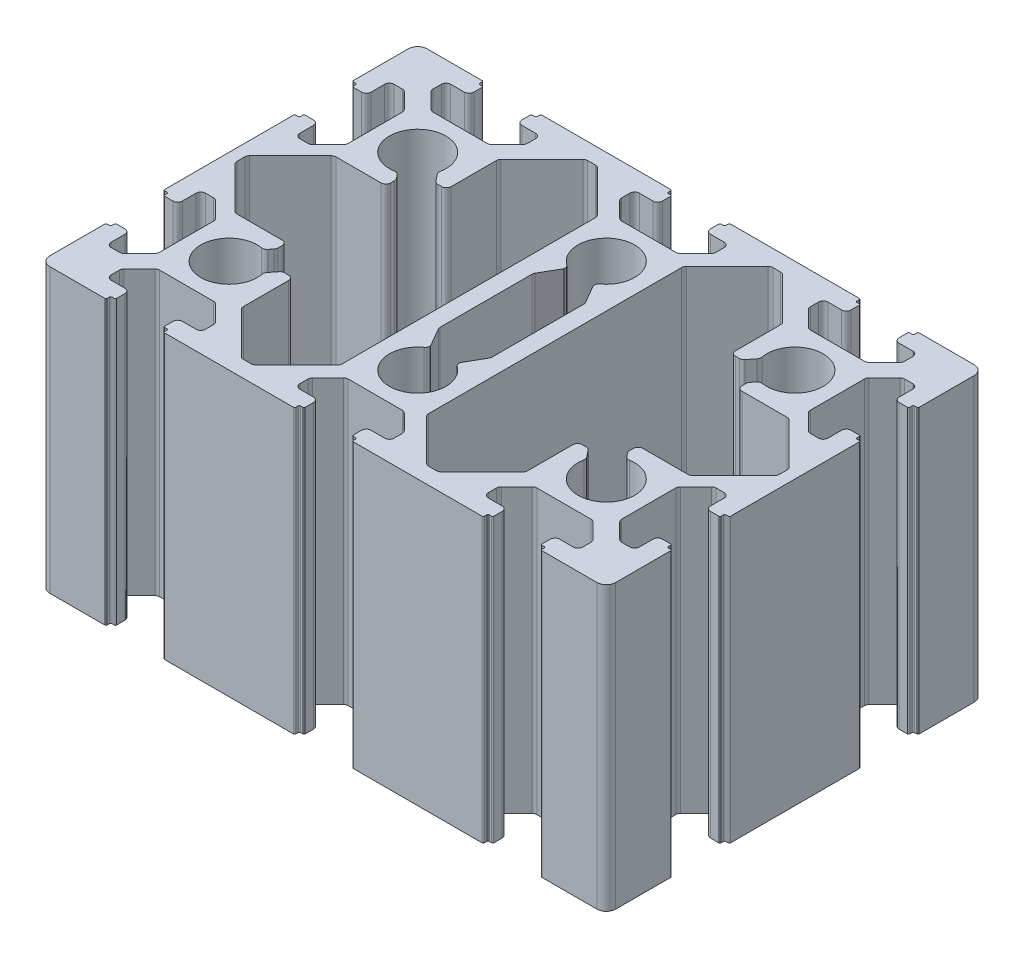
SolidWorks part; units mm, degrees
material "6061 Alloy"
ref_plane "Front Plane" through (0, 0, 0) normal (0, 0, 1) x (1, 0, 0)
ref_plane "Top Plane" through (0, 0, 0) normal (0, 1, 0) x (1, 0, 0)
ref_plane "Right Plane" through (0, 0, 0) normal (1, 0, 0) x (0, 0, -1)
sketch "Sketch2" plane through (0, 0, 0) normal (0, 1, 0) x (1, 0, 0)
  line L1 (60, -40) -> (-60, -40) construction
  line L2 (60, -40) -> (60, 40) construction
  line L3 (60, 40) -> (-60, 40) construction
  line L4 (-60, -40) -> (-60, 40) construction
  line L5 (60, -40) -> (-60, 40) construction
  line L6 (60, 40) -> (-60, -40) construction
  point P0 (0, 0)
  dimension "D1" = 120
  dimension "D2" = 80
sketch "Sketch5" plane through (0, 0, 0) normal (0, 1, 0) x (1, 0, 0)
  line L0 (0, 40) -> (0, -40) construction
  line L1 (60, 40) -> (-60, 40) construction
  line L2 (60, -40) -> (-60, -40) construction
  line L3 (-60, 0) -> (60, 0) construction
  line L4 (-60, -40) -> (-60, 40) construction
  line L5 (0, 40) -> (0, 29)
  line L6 (5.7358, 29) -> (-5.7358, 29)
  line L7 (-6.4429, 29.2929) -> (-9.7071, 32.5571)
  line L8 (-10, 33.2642) -> (-10, 35)
  line L9 (-9, 36) -> (-6.1, 36)
  line L10 (-5.1, 37) -> (-5.1, 38.75)
  line L11 (-5.35, 39) -> (-5.85, 39)
  line L12 (-6.1, 39.25) -> (-6.1, 39.75)
  line L13 (-6.35, 40) -> (-33.65, 40)
  line L14 (-33.9, 39.75) -> (-33.9, 39.25)
  line L15 (-34.15, 39) -> (-34.65, 39)
  line L16 (-34.9, 38.75) -> (-34.9, 37)
  line L17 (-33.9, 36) -> (-31, 36)
  line L18 (-30, 35) -> (-30, 33.2642)
  line L19 (-30.2929, 32.5571) -> (-33.5571, 29.2929)
  line L20 (-34.2642, 29) -> (-45.7358, 29)
  line L21 (-46.4429, 29.2929) -> (-49.7071, 32.5571)
  line L22 (-50, 33.2642) -> (-50, 35)
  line L23 (-49, 36) -> (-46.1, 36)
  line L24 (-45.1, 37) -> (-45.1, 38.75)
  line L25 (-45.35, 39) -> (-45.85, 39)
  line L26 (-46.1, 39.25) -> (-46.1, 39.75)
  line L27 (-46.35, 40) -> (-58, 40)
  line L28 (-60, 38) -> (-60, 26.35)
  line L29 (-59.75, 26.1) -> (-59.25, 26.1)
  line L30 (-59, 25.85) -> (-59, 25.35)
  line L31 (-58.75, 25.1) -> (-57, 25.1)
  line L32 (-56, 26.1) -> (-56, 29)
  line L33 (-55, 30) -> (-53.2642, 30)
  line L34 (-52.5571, 29.7071) -> (-49.2929, 26.4429)
  line L35 (-49, 25.7358) -> (-49, 14.2642)
  line L36 (-49.2929, 13.5571) -> (-52.5571, 10.2929)
  line L37 (-53.2642, 10) -> (-55, 10)
  line L38 (-56, 11) -> (-56, 13.9)
  line L39 (-57, 14.9) -> (-58.75, 14.9)
  line L40 (-59, 14.65) -> (-59, 14.15)
  line L41 (-59.25, 13.9) -> (-59.75, 13.9)
  line L42 (-60, 13.65) -> (-60, -13.65)
  line L43 (-40, 29) -> (-40, 40) construction
  line L44 (-49, 20) -> (-60, 20) construction
  line L45 (-60, 0) -> (-57.5, 0)
  line L46 (-57.5, -0.8358) -> (-57.5, 0.8358)
  line L47 (-57.2071, 1.5429) -> (-48.5429, 10.2071)
  line L48 (-47.8358, 10.5) -> (-38.25, 10.5)
  line L49 (-37.25, 11.5) -> (-37.25, 12.3383)
  line L50 (-40, 20) -> (-20, 0) construction
  line L51 (-34.2044, 18.4471) -> (-40, 20) construction
  line L52 (-30.15, 17.25) -> (-30.15, 26.8358)
  line L53 (-29.8571, 27.5429) -> (-21.1929, 36.2071)
  line L54 (-20.4858, 36.5) -> (-18.8142, 36.5)
  line L55 (-18.1071, 36.2071) -> (-9.4429, 27.5429)
  line L56 (-9.15, 26.8358) -> (-9.15, -26.8358)
  line L57 (-40, 20) -> (-38.4471, 14.2044) construction
  line L58 (-40, 20) -> (-44.2426, 24.2426) construction
  line L59 (-38.0611, 13.7145) -> (-37.4645, 12.9572)
  line L60 (-33.909, 18.0721) -> (-32.7739, 16.6312)
  line L61 (-31.9883, 16.25) -> (-31.15, 16.25)
  line L62 (-9.15, 0) -> (-5.5, 0) construction
  line L63 (-5.5, -9.7321) -> (-5.5, 9.7321)
  line L64 (-5.366, 10.2321) -> (-3.1188, 14.1243)
  line L65 (-3.1188, 14.1243) -> (-3.1188, 14.34)
  line L66 (0, 29) -> (0, 26) construction
  line L67 (-40, -20) -> (-44.2426, -24.2426) construction
  line L68 (-40, -20) -> (-38.4471, -14.2044) construction
  line L69 (-34.2044, -18.4471) -> (-40, -20) construction
  line L70 (-40, -20) -> (-20, 0) construction
  line L71 (-49, -20) -> (-60, -20) construction
  line L72 (-40, -29) -> (-40, -40) construction
  line L73 (0, -29) -> (0, -26) construction
  line L74 (-3.1188, -14.1243) -> (-3.1188, -14.34)
  line L75 (-5.366, -10.2321) -> (-3.1188, -14.1243)
  line L76 (-31.9883, -16.25) -> (-31.15, -16.25)
  line L77 (-33.909, -18.0721) -> (-32.7739, -16.6312)
  line L78 (-38.0611, -13.7145) -> (-37.4645, -12.9572)
  line L79 (-18.1071, -36.2071) -> (-9.4429, -27.5429)
  line L80 (-20.4858, -36.5) -> (-18.8142, -36.5)
  line L81 (-29.8571, -27.5429) -> (-21.1929, -36.2071)
  line L82 (-30.15, -17.25) -> (-30.15, -26.8358)
  line L83 (-37.25, -11.5) -> (-37.25, -12.3383)
  line L84 (-47.8358, -10.5) -> (-38.25, -10.5)
  line L85 (-57.2071, -1.5429) -> (-48.5429, -10.2071)
  line L86 (-59.25, -13.9) -> (-59.75, -13.9)
  line L87 (-59, -14.65) -> (-59, -14.15)
  line L88 (-57, -14.9) -> (-58.75, -14.9)
  line L89 (-56, -11) -> (-56, -13.9)
  line L90 (-53.2642, -10) -> (-55, -10)
  line L91 (-49.2929, -13.5571) -> (-52.5571, -10.2929)
  line L92 (-49, -25.7358) -> (-49, -14.2642)
  line L93 (-52.5571, -29.7071) -> (-49.2929, -26.4429)
  line L94 (-55, -30) -> (-53.2642, -30)
  line L95 (-56, -26.1) -> (-56, -29)
  line L96 (-58.75, -25.1) -> (-57, -25.1)
  line L97 (-59, -25.85) -> (-59, -25.35)
  line L98 (-59.75, -26.1) -> (-59.25, -26.1)
  line L99 (-60, -38) -> (-60, -26.35)
  line L100 (-46.35, -40) -> (-58, -40)
  line L101 (-46.1, -39.25) -> (-46.1, -39.75)
  line L102 (-45.35, -39) -> (-45.85, -39)
  line L103 (-45.1, -37) -> (-45.1, -38.75)
  line L104 (-49, -36) -> (-46.1, -36)
  line L105 (-50, -33.2642) -> (-50, -35)
  line L106 (-46.4429, -29.2929) -> (-49.7071, -32.5571)
  line L107 (-34.2642, -29) -> (-45.7358, -29)
  line L108 (-30.2929, -32.5571) -> (-33.5571, -29.2929)
  line L109 (-30, -35) -> (-30, -33.2642)
  line L110 (-33.9, -36) -> (-31, -36)
  line L111 (-34.9, -38.75) -> (-34.9, -37)
  line L112 (-34.15, -39) -> (-34.65, -39)
  line L113 (-33.9, -39.75) -> (-33.9, -39.25)
  line L114 (-6.35, -40) -> (-33.65, -40)
  line L115 (-6.1, -39.25) -> (-6.1, -39.75)
  line L116 (-5.35, -39) -> (-5.85, -39)
  line L117 (-5.1, -37) -> (-5.1, -38.75)
  line L118 (-9, -36) -> (-6.1, -36)
  line L119 (-10, -33.2642) -> (-10, -35)
  line L120 (-6.4429, -29.2929) -> (-9.7071, -32.5571)
  line L121 (5.7358, -29) -> (-5.7358, -29)
  line L122 (0, -40) -> (0, -29)
  line L123 (40, -29) -> (40, -40) construction
  line L124 (49, -20) -> (60, -20) construction
  line L125 (40, -20) -> (20, 0) construction
  line L126 (34.2044, -18.4471) -> (40, -20) construction
  line L127 (40, -20) -> (38.4471, -14.2044) construction
  line L128 (40, -20) -> (44.2426, -24.2426) construction
  line L129 (40, 20) -> (44.2426, 24.2426) construction
  line L130 (40, 20) -> (38.4471, 14.2044) construction
  line L131 (34.2044, 18.4471) -> (40, 20) construction
  line L132 (40, 20) -> (20, 0) construction
  line L133 (49, 20) -> (60, 20) construction
  line L134 (40, 29) -> (40, 40) construction
  line L135 (6.4429, -29.2929) -> (9.7071, -32.5571)
  line L136 (10, -33.2642) -> (10, -35)
  line L137 (9, -36) -> (6.1, -36)
  line L138 (5.1, -37) -> (5.1, -38.75)
  line L139 (5.35, -39) -> (5.85, -39)
  line L140 (6.1, -39.25) -> (6.1, -39.75)
  line L141 (6.35, -40) -> (33.65, -40)
  line L142 (33.9, -39.75) -> (33.9, -39.25)
  line L143 (34.15, -39) -> (34.65, -39)
  line L144 (34.9, -38.75) -> (34.9, -37)
  line L145 (33.9, -36) -> (31, -36)
  line L146 (30, -35) -> (30, -33.2642)
  line L147 (30.2929, -32.5571) -> (33.5571, -29.2929)
  line L148 (34.2642, -29) -> (45.7358, -29)
  line L149 (46.4429, -29.2929) -> (49.7071, -32.5571)
  line L150 (50, -33.2642) -> (50, -35)
  line L151 (49, -36) -> (46.1, -36)
  line L152 (45.1, -37) -> (45.1, -38.75)
  line L153 (45.35, -39) -> (45.85, -39)
  line L154 (46.1, -39.25) -> (46.1, -39.75)
  line L155 (46.35, -40) -> (58, -40)
  line L156 (60, -38) -> (60, -26.35)
  line L157 (59.75, -26.1) -> (59.25, -26.1)
  line L158 (59, -25.85) -> (59, -25.35)
  line L159 (58.75, -25.1) -> (57, -25.1)
  line L160 (56, -26.1) -> (56, -29)
  line L161 (55, -30) -> (53.2642, -30)
  line L162 (52.5571, -29.7071) -> (49.2929, -26.4429)
  line L163 (49, -25.7358) -> (49, -14.2642)
  line L164 (49.2929, -13.5571) -> (52.5571, -10.2929)
  line L165 (53.2642, -10) -> (55, -10)
  line L166 (56, -11) -> (56, -13.9)
  line L167 (57, -14.9) -> (58.75, -14.9)
  line L168 (59, -14.65) -> (59, -14.15)
  line L169 (59.25, -13.9) -> (59.75, -13.9)
  line L170 (57.2071, -1.5429) -> (48.5429, -10.2071)
  line L171 (47.8358, -10.5) -> (38.25, -10.5)
  line L172 (37.25, -11.5) -> (37.25, -12.3383)
  line L173 (30.15, -17.25) -> (30.15, -26.8358)
  line L174 (29.8571, -27.5429) -> (21.1929, -36.2071)
  line L175 (20.4858, -36.5) -> (18.8142, -36.5)
  line L176 (18.1071, -36.2071) -> (9.4429, -27.5429)
  line L177 (38.0611, -13.7145) -> (37.4645, -12.9572)
  line L178 (33.909, -18.0721) -> (32.7739, -16.6312)
  line L179 (31.9883, -16.25) -> (31.15, -16.25)
  line L180 (5.366, -10.2321) -> (3.1188, -14.1243)
  line L181 (3.1188, -14.1243) -> (3.1188, -14.34)
  line L182 (3.1188, 14.1243) -> (3.1188, 14.34)
  line L183 (5.366, 10.2321) -> (3.1188, 14.1243)
  line L184 (5.5, -9.7321) -> (5.5, 9.7321)
  line L185 (9.15, 0) -> (5.5, 0) construction
  line L186 (31.9883, 16.25) -> (31.15, 16.25)
  line L187 (33.909, 18.0721) -> (32.7739, 16.6312)
  line L188 (38.0611, 13.7145) -> (37.4645, 12.9572)
  line L189 (9.15, 26.8358) -> (9.15, -26.8358)
  line L190 (18.1071, 36.2071) -> (9.4429, 27.5429)
  line L191 (20.4858, 36.5) -> (18.8142, 36.5)
  line L192 (29.8571, 27.5429) -> (21.1929, 36.2071)
  line L193 (30.15, 17.25) -> (30.15, 26.8358)
  line L194 (37.25, 11.5) -> (37.25, 12.3383)
  line L195 (47.8358, 10.5) -> (38.25, 10.5)
  line L196 (57.2071, 1.5429) -> (48.5429, 10.2071)
  line L197 (57.5, -0.8358) -> (57.5, 0.8358)
  line L198 (60, 0) -> (57.5, 0)
  line L199 (60, 13.65) -> (60, -13.65)
  line L200 (59.25, 13.9) -> (59.75, 13.9)
  line L201 (59, 14.65) -> (59, 14.15)
  line L202 (57, 14.9) -> (58.75, 14.9)
  line L203 (56, 11) -> (56, 13.9)
  line L204 (53.2642, 10) -> (55, 10)
  line L205 (49.2929, 13.5571) -> (52.5571, 10.2929)
  line L206 (49, 25.7358) -> (49, 14.2642)
  line L207 (52.5571, 29.7071) -> (49.2929, 26.4429)
  line L208 (55, 30) -> (53.2642, 30)
  line L209 (56, 26.1) -> (56, 29)
  line L210 (58.75, 25.1) -> (57, 25.1)
  line L211 (59, 25.85) -> (59, 25.35)
  line L212 (59.75, 26.1) -> (59.25, 26.1)
  line L213 (60, 38) -> (60, 26.35)
  line L214 (46.35, 40) -> (58, 40)
  line L215 (46.1, 39.25) -> (46.1, 39.75)
  line L216 (45.35, 39) -> (45.85, 39)
  line L217 (45.1, 37) -> (45.1, 38.75)
  line L218 (49, 36) -> (46.1, 36)
  line L219 (50, 33.2642) -> (50, 35)
  line L220 (46.4429, 29.2929) -> (49.7071, 32.5571)
  line L221 (34.2642, 29) -> (45.7358, 29)
  line L222 (30.2929, 32.5571) -> (33.5571, 29.2929)
  line L223 (30, 35) -> (30, 33.2642)
  line L224 (33.9, 36) -> (31, 36)
  line L225 (34.9, 38.75) -> (34.9, 37)
  line L226 (34.15, 39) -> (34.65, 39)
  line L227 (33.9, 39.75) -> (33.9, 39.25)
  line L228 (6.35, 40) -> (33.65, 40)
  line L229 (6.1, 39.25) -> (6.1, 39.75)
  line L230 (5.35, 39) -> (5.85, 39)
  line L231 (5.1, 37) -> (5.1, 38.75)
  line L232 (9, 36) -> (6.1, 36)
  line L233 (10, 33.2642) -> (10, 35)
  line L234 (6.4429, 29.2929) -> (9.7071, 32.5571)
  arc A0 (-34.1059, 18.8779) -> (-39.0114, 14.082) centre (-40, 20) ccw
  arc A1 (3.5304, 15.1486) -> (-3.5304, 15.1486) centre (0, 20) ccw
  arc A2 (-56, 13.9) -> (-57, 14.9) centre (-57, 13.9) ccw
  arc A3 (-6.1, 36) -> (-5.1, 37) centre (-6.1, 37) ccw
  arc A4 (-5.7358, 29) -> (-6.4429, 29.2929) centre (-5.7358, 30) cw
  arc A5 (-9.7071, 32.5571) -> (-10, 33.2642) centre (-9, 33.2642) cw
  arc A6 (-10, 35) -> (-9, 36) centre (-9, 35) cw
  arc A7 (-5.5, 9.7321) -> (-5.366, 10.2321) centre (-4.5, 9.7321) cw
  arc A8 (-3.1188, 14.34) -> (-3.5304, 15.1486) centre (-4.1188, 14.34) ccw
  arc A9 (-39.0114, 14.082) -> (-38.0611, 13.7145) centre (-38.8466, 13.0957) cw
  arc A10 (-37.25, 12.3383) -> (-37.4645, 12.9572) centre (-38.25, 12.3383) ccw
  arc A11 (-38.25, 10.5) -> (-37.25, 11.5) centre (-38.25, 11.5) ccw
  arc A12 (-34.1059, 18.8779) -> (-33.909, 18.0721) centre (-33.1235, 18.6909) ccw
  arc A13 (-32.7739, 16.6312) -> (-31.9883, 16.25) centre (-31.9883, 17.25) ccw
  arc A14 (-31.15, 16.25) -> (-30.15, 17.25) centre (-31.15, 17.25) ccw
  arc A15 (-48.5429, 10.2071) -> (-47.8358, 10.5) centre (-47.8358, 9.5) cw
  arc A16 (-18.8142, 36.5) -> (-18.1071, 36.2071) centre (-18.8142, 35.5) cw
  arc A17 (-21.1929, 36.2071) -> (-20.4858, 36.5) centre (-20.4858, 35.5) cw
  arc A18 (-30.15, 26.8358) -> (-29.8571, 27.5429) centre (-29.15, 26.8358) cw
  arc A19 (-9.4429, 27.5429) -> (-9.15, 26.8358) centre (-10.15, 26.8358) cw
  arc A20 (-34.9, 37) -> (-33.9, 36) centre (-33.9, 37) ccw
  arc A21 (-46.1, 36) -> (-45.1, 37) centre (-46.1, 37) ccw
  arc A22 (-30, 33.2642) -> (-30.2929, 32.5571) centre (-31, 33.2642) cw
  arc A23 (-31, 36) -> (-30, 35) centre (-31, 35) cw
  arc A24 (-50, 35) -> (-49, 36) centre (-49, 35) cw
  arc A25 (-49.7071, 32.5571) -> (-50, 33.2642) centre (-49, 33.2642) cw
  arc A26 (-45.7358, 29) -> (-46.4429, 29.2929) centre (-45.7358, 30) cw
  arc A27 (-33.5571, 29.2929) -> (-34.2642, 29) centre (-34.2642, 30) cw
  arc A28 (-57, 25.1) -> (-56, 26.1) centre (-57, 26.1) ccw
  arc A29 (-56, 29) -> (-55, 30) centre (-55, 29) cw
  arc A30 (-53.2642, 30) -> (-52.5571, 29.7071) centre (-53.2642, 29) cw
  arc A31 (-49.2929, 26.4429) -> (-49, 25.7358) centre (-50, 25.7358) cw
  arc A32 (-49, 14.2642) -> (-49.2929, 13.5571) centre (-50, 14.2642) cw
  arc A33 (-52.5571, 10.2929) -> (-53.2642, 10) centre (-53.2642, 11) cw
  arc A34 (-55, 10) -> (-56, 11) centre (-55, 11) cw
  arc A35 (-6.1, 39.75) -> (-6.35, 40) centre (-6.35, 39.75) ccw
  arc A36 (-5.85, 39) -> (-6.1, 39.25) centre (-5.85, 39.25) cw
  arc A37 (-5.1, 38.75) -> (-5.35, 39) centre (-5.35, 38.75) ccw
  arc A38 (-33.65, 40) -> (-33.9, 39.75) centre (-33.65, 39.75) ccw
  arc A39 (-34.65, 39) -> (-34.9, 38.75) centre (-34.65, 38.75) ccw
  arc A40 (-33.9, 39.25) -> (-34.15, 39) centre (-34.15, 39.25) cw
  arc A41 (-46.1, 39.75) -> (-46.35, 40) centre (-46.35, 39.75) ccw
  arc A42 (-45.85, 39) -> (-46.1, 39.25) centre (-45.85, 39.25) cw
  arc A43 (-45.1, 38.75) -> (-45.35, 39) centre (-45.35, 38.75) ccw
  arc A44 (-60, 26.35) -> (-59.75, 26.1) centre (-59.75, 26.35) ccw
  arc A45 (-59.25, 26.1) -> (-59, 25.85) centre (-59.25, 25.85) cw
  arc A46 (-59, 25.35) -> (-58.75, 25.1) centre (-58.75, 25.35) ccw
  arc A47 (-58.75, 14.9) -> (-59, 14.65) centre (-58.75, 14.65) ccw
  arc A48 (-59, 14.15) -> (-59.25, 13.9) centre (-59.25, 14.15) cw
  arc A49 (-59.75, 13.9) -> (-60, 13.65) centre (-59.75, 13.65) ccw
  arc A50 (-57.5, 0.8358) -> (-57.2071, 1.5429) centre (-56.5, 0.8358) cw
  arc A51 (-58, 40) -> (-60, 38) centre (-58, 38) ccw
  arc A52 (-58, -40) -> (-60, -38) centre (-58, -38) cw
  arc A53 (-57.5, -0.8358) -> (-57.2071, -1.5429) centre (-56.5, -0.8358) ccw
  arc A54 (-59.75, -13.9) -> (-60, -13.65) centre (-59.75, -13.65) cw
  arc A55 (-59, -14.15) -> (-59.25, -13.9) centre (-59.25, -14.15) ccw
  arc A56 (-58.75, -14.9) -> (-59, -14.65) centre (-58.75, -14.65) cw
  arc A57 (-59, -25.35) -> (-58.75, -25.1) centre (-58.75, -25.35) cw
  arc A58 (-59.25, -26.1) -> (-59, -25.85) centre (-59.25, -25.85) ccw
  arc A59 (-60, -26.35) -> (-59.75, -26.1) centre (-59.75, -26.35) cw
  arc A60 (-45.1, -38.75) -> (-45.35, -39) centre (-45.35, -38.75) cw
  arc A61 (-45.85, -39) -> (-46.1, -39.25) centre (-45.85, -39.25) ccw
  arc A62 (-46.1, -39.75) -> (-46.35, -40) centre (-46.35, -39.75) cw
  arc A63 (-33.9, -39.25) -> (-34.15, -39) centre (-34.15, -39.25) ccw
  arc A64 (-34.65, -39) -> (-34.9, -38.75) centre (-34.65, -38.75) cw
  arc A65 (-33.65, -40) -> (-33.9, -39.75) centre (-33.65, -39.75) cw
  arc A66 (-5.1, -38.75) -> (-5.35, -39) centre (-5.35, -38.75) cw
  arc A67 (-5.85, -39) -> (-6.1, -39.25) centre (-5.85, -39.25) ccw
  arc A68 (-6.1, -39.75) -> (-6.35, -40) centre (-6.35, -39.75) cw
  arc A69 (-55, -10) -> (-56, -11) centre (-55, -11) ccw
  arc A70 (-52.5571, -10.2929) -> (-53.2642, -10) centre (-53.2642, -11) ccw
  arc A71 (-49, -14.2642) -> (-49.2929, -13.5571) centre (-50, -14.2642) ccw
  arc A72 (-49.2929, -26.4429) -> (-49, -25.7358) centre (-50, -25.7358) ccw
  arc A73 (-53.2642, -30) -> (-52.5571, -29.7071) centre (-53.2642, -29) ccw
  arc A74 (-56, -29) -> (-55, -30) centre (-55, -29) ccw
  arc A75 (-57, -25.1) -> (-56, -26.1) centre (-57, -26.1) cw
  arc A76 (-33.5571, -29.2929) -> (-34.2642, -29) centre (-34.2642, -30) ccw
  arc A77 (-45.7358, -29) -> (-46.4429, -29.2929) centre (-45.7358, -30) ccw
  arc A78 (-49.7071, -32.5571) -> (-50, -33.2642) centre (-49, -33.2642) ccw
  arc A79 (-50, -35) -> (-49, -36) centre (-49, -35) ccw
  arc A80 (-31, -36) -> (-30, -35) centre (-31, -35) ccw
  arc A81 (-30, -33.2642) -> (-30.2929, -32.5571) centre (-31, -33.2642) ccw
  arc A82 (-46.1, -36) -> (-45.1, -37) centre (-46.1, -37) cw
  arc A83 (-34.9, -37) -> (-33.9, -36) centre (-33.9, -37) cw
  arc A84 (-9.4429, -27.5429) -> (-9.15, -26.8358) centre (-10.15, -26.8358) ccw
  arc A85 (-30.15, -26.8358) -> (-29.8571, -27.5429) centre (-29.15, -26.8358) ccw
  arc A86 (-21.1929, -36.2071) -> (-20.4858, -36.5) centre (-20.4858, -35.5) ccw
  arc A87 (-18.8142, -36.5) -> (-18.1071, -36.2071) centre (-18.8142, -35.5) ccw
  arc A88 (-48.5429, -10.2071) -> (-47.8358, -10.5) centre (-47.8358, -9.5) ccw
  arc A89 (-31.15, -16.25) -> (-30.15, -17.25) centre (-31.15, -17.25) cw
  arc A90 (-32.7739, -16.6312) -> (-31.9883, -16.25) centre (-31.9883, -17.25) cw
  arc A91 (-34.1059, -18.8779) -> (-33.909, -18.0721) centre (-33.1235, -18.6909) cw
  arc A92 (-38.25, -10.5) -> (-37.25, -11.5) centre (-38.25, -11.5) cw
  arc A93 (-37.25, -12.3383) -> (-37.4645, -12.9572) centre (-38.25, -12.3383) cw
  arc A94 (-39.0114, -14.082) -> (-38.0611, -13.7145) centre (-38.8466, -13.0957) ccw
  arc A95 (-3.1188, -14.34) -> (-3.5304, -15.1486) centre (-4.1188, -14.34) cw
  arc A96 (-5.5, -9.7321) -> (-5.366, -10.2321) centre (-4.5, -9.7321) ccw
  arc A97 (-10, -35) -> (-9, -36) centre (-9, -35) ccw
  arc A98 (-9.7071, -32.5571) -> (-10, -33.2642) centre (-9, -33.2642) ccw
  arc A99 (-5.7358, -29) -> (-6.4429, -29.2929) centre (-5.7358, -30) ccw
  arc A100 (-6.1, -36) -> (-5.1, -37) centre (-6.1, -37) cw
  arc A101 (-56, -13.9) -> (-57, -14.9) centre (-57, -13.9) cw
  arc A102 (3.5304, -15.1486) -> (-3.5304, -15.1486) centre (0, -20) cw
  arc A103 (-34.1059, -18.8779) -> (-39.0114, -14.082) centre (-40, -20) cw
  arc A104 (34.1059, -18.8779) -> (39.0114, -14.082) centre (40, -20) ccw
  arc A105 (56, -13.9) -> (57, -14.9) centre (57, -13.9) ccw
  arc A106 (6.1, -36) -> (5.1, -37) centre (6.1, -37) ccw
  arc A107 (5.7358, -29) -> (6.4429, -29.2929) centre (5.7358, -30) cw
  arc A108 (9.7071, -32.5571) -> (10, -33.2642) centre (9, -33.2642) cw
  arc A109 (10, -35) -> (9, -36) centre (9, -35) cw
  arc A110 (5.5, -9.7321) -> (5.366, -10.2321) centre (4.5, -9.7321) cw
  arc A111 (3.1188, -14.34) -> (3.5304, -15.1486) centre (4.1188, -14.34) ccw
  arc A112 (39.0114, -14.082) -> (38.0611, -13.7145) centre (38.8466, -13.0957) cw
  arc A113 (37.25, -12.3383) -> (37.4645, -12.9572) centre (38.25, -12.3383) ccw
  arc A114 (38.25, -10.5) -> (37.25, -11.5) centre (38.25, -11.5) ccw
  arc A115 (34.1059, -18.8779) -> (33.909, -18.0721) centre (33.1235, -18.6909) ccw
  arc A116 (32.7739, -16.6312) -> (31.9883, -16.25) centre (31.9883, -17.25) ccw
  arc A117 (31.15, -16.25) -> (30.15, -17.25) centre (31.15, -17.25) ccw
  arc A118 (48.5429, -10.2071) -> (47.8358, -10.5) centre (47.8358, -9.5) cw
  arc A119 (18.8142, -36.5) -> (18.1071, -36.2071) centre (18.8142, -35.5) cw
  arc A120 (21.1929, -36.2071) -> (20.4858, -36.5) centre (20.4858, -35.5) cw
  arc A121 (30.15, -26.8358) -> (29.8571, -27.5429) centre (29.15, -26.8358) cw
  arc A122 (9.4429, -27.5429) -> (9.15, -26.8358) centre (10.15, -26.8358) cw
  arc A123 (34.9, -37) -> (33.9, -36) centre (33.9, -37) ccw
  arc A124 (46.1, -36) -> (45.1, -37) centre (46.1, -37) ccw
  arc A125 (30, -33.2642) -> (30.2929, -32.5571) centre (31, -33.2642) cw
  arc A126 (31, -36) -> (30, -35) centre (31, -35) cw
  arc A127 (50, -35) -> (49, -36) centre (49, -35) cw
  arc A128 (49.7071, -32.5571) -> (50, -33.2642) centre (49, -33.2642) cw
  arc A129 (45.7358, -29) -> (46.4429, -29.2929) centre (45.7358, -30) cw
  arc A130 (33.5571, -29.2929) -> (34.2642, -29) centre (34.2642, -30) cw
  arc A131 (57, -25.1) -> (56, -26.1) centre (57, -26.1) ccw
  arc A132 (56, -29) -> (55, -30) centre (55, -29) cw
  arc A133 (53.2642, -30) -> (52.5571, -29.7071) centre (53.2642, -29) cw
  arc A134 (49.2929, -26.4429) -> (49, -25.7358) centre (50, -25.7358) cw
  arc A135 (49, -14.2642) -> (49.2929, -13.5571) centre (50, -14.2642) cw
  arc A136 (52.5571, -10.2929) -> (53.2642, -10) centre (53.2642, -11) cw
  arc A137 (55, -10) -> (56, -11) centre (55, -11) cw
  arc A138 (6.1, -39.75) -> (6.35, -40) centre (6.35, -39.75) ccw
  arc A139 (5.85, -39) -> (6.1, -39.25) centre (5.85, -39.25) cw
  arc A140 (5.1, -38.75) -> (5.35, -39) centre (5.35, -38.75) ccw
  arc A141 (33.65, -40) -> (33.9, -39.75) centre (33.65, -39.75) ccw
  arc A142 (34.65, -39) -> (34.9, -38.75) centre (34.65, -38.75) ccw
  arc A143 (33.9, -39.25) -> (34.15, -39) centre (34.15, -39.25) cw
  arc A144 (46.1, -39.75) -> (46.35, -40) centre (46.35, -39.75) ccw
  arc A145 (45.85, -39) -> (46.1, -39.25) centre (45.85, -39.25) cw
  arc A146 (45.1, -38.75) -> (45.35, -39) centre (45.35, -38.75) ccw
  arc A147 (60, -26.35) -> (59.75, -26.1) centre (59.75, -26.35) ccw
  arc A148 (59.25, -26.1) -> (59, -25.85) centre (59.25, -25.85) cw
  arc A149 (59, -25.35) -> (58.75, -25.1) centre (58.75, -25.35) ccw
  arc A150 (58.75, -14.9) -> (59, -14.65) centre (58.75, -14.65) ccw
  arc A151 (59, -14.15) -> (59.25, -13.9) centre (59.25, -14.15) cw
  arc A152 (59.75, -13.9) -> (60, -13.65) centre (59.75, -13.65) ccw
  arc A153 (57.5, -0.8358) -> (57.2071, -1.5429) centre (56.5, -0.8358) cw
  arc A154 (58, -40) -> (60, -38) centre (58, -38) ccw
  arc A155 (58, 40) -> (60, 38) centre (58, 38) cw
  arc A156 (57.5, 0.8358) -> (57.2071, 1.5429) centre (56.5, 0.8358) ccw
  arc A157 (59.75, 13.9) -> (60, 13.65) centre (59.75, 13.65) cw
  arc A158 (59, 14.15) -> (59.25, 13.9) centre (59.25, 14.15) ccw
  arc A159 (58.75, 14.9) -> (59, 14.65) centre (58.75, 14.65) cw
  arc A160 (59, 25.35) -> (58.75, 25.1) centre (58.75, 25.35) cw
  arc A161 (59.25, 26.1) -> (59, 25.85) centre (59.25, 25.85) ccw
  arc A162 (60, 26.35) -> (59.75, 26.1) centre (59.75, 26.35) cw
  arc A163 (45.1, 38.75) -> (45.35, 39) centre (45.35, 38.75) cw
  arc A164 (45.85, 39) -> (46.1, 39.25) centre (45.85, 39.25) ccw
  arc A165 (46.1, 39.75) -> (46.35, 40) centre (46.35, 39.75) cw
  arc A166 (33.9, 39.25) -> (34.15, 39) centre (34.15, 39.25) ccw
  arc A167 (34.65, 39) -> (34.9, 38.75) centre (34.65, 38.75) cw
  arc A168 (33.65, 40) -> (33.9, 39.75) centre (33.65, 39.75) cw
  arc A169 (5.1, 38.75) -> (5.35, 39) centre (5.35, 38.75) cw
  arc A170 (5.85, 39) -> (6.1, 39.25) centre (5.85, 39.25) ccw
  arc A171 (6.1, 39.75) -> (6.35, 40) centre (6.35, 39.75) cw
  arc A172 (55, 10) -> (56, 11) centre (55, 11) ccw
  arc A173 (52.5571, 10.2929) -> (53.2642, 10) centre (53.2642, 11) ccw
  arc A174 (49, 14.2642) -> (49.2929, 13.5571) centre (50, 14.2642) ccw
  arc A175 (49.2929, 26.4429) -> (49, 25.7358) centre (50, 25.7358) ccw
  arc A176 (53.2642, 30) -> (52.5571, 29.7071) centre (53.2642, 29) ccw
  arc A177 (56, 29) -> (55, 30) centre (55, 29) ccw
  arc A178 (57, 25.1) -> (56, 26.1) centre (57, 26.1) cw
  arc A179 (33.5571, 29.2929) -> (34.2642, 29) centre (34.2642, 30) ccw
  arc A180 (45.7358, 29) -> (46.4429, 29.2929) centre (45.7358, 30) ccw
  arc A181 (49.7071, 32.5571) -> (50, 33.2642) centre (49, 33.2642) ccw
  arc A182 (50, 35) -> (49, 36) centre (49, 35) ccw
  arc A183 (31, 36) -> (30, 35) centre (31, 35) ccw
  arc A184 (30, 33.2642) -> (30.2929, 32.5571) centre (31, 33.2642) ccw
  arc A185 (46.1, 36) -> (45.1, 37) centre (46.1, 37) cw
  arc A186 (34.9, 37) -> (33.9, 36) centre (33.9, 37) cw
  arc A187 (9.4429, 27.5429) -> (9.15, 26.8358) centre (10.15, 26.8358) ccw
  arc A188 (30.15, 26.8358) -> (29.8571, 27.5429) centre (29.15, 26.8358) ccw
  arc A189 (21.1929, 36.2071) -> (20.4858, 36.5) centre (20.4858, 35.5) ccw
  arc A190 (18.8142, 36.5) -> (18.1071, 36.2071) centre (18.8142, 35.5) ccw
  arc A191 (48.5429, 10.2071) -> (47.8358, 10.5) centre (47.8358, 9.5) ccw
  arc A192 (31.15, 16.25) -> (30.15, 17.25) centre (31.15, 17.25) cw
  arc A193 (32.7739, 16.6312) -> (31.9883, 16.25) centre (31.9883, 17.25) cw
  arc A194 (34.1059, 18.8779) -> (33.909, 18.0721) centre (33.1235, 18.6909) cw
  arc A195 (38.25, 10.5) -> (37.25, 11.5) centre (38.25, 11.5) cw
  arc A196 (37.25, 12.3383) -> (37.4645, 12.9572) centre (38.25, 12.3383) cw
  arc A197 (39.0114, 14.082) -> (38.0611, 13.7145) centre (38.8466, 13.0957) ccw
  arc A198 (3.1188, 14.34) -> (3.5304, 15.1486) centre (4.1188, 14.34) cw
  arc A199 (5.5, 9.7321) -> (5.366, 10.2321) centre (4.5, 9.7321) ccw
  arc A200 (10, 35) -> (9, 36) centre (9, 35) ccw
  arc A201 (9.7071, 32.5571) -> (10, 33.2642) centre (9, 33.2642) ccw
  arc A202 (5.7358, 29) -> (6.4429, 29.2929) centre (5.7358, 30) ccw
  arc A203 (6.1, 36) -> (5.1, 37) centre (6.1, 37) cw
  arc A204 (56, 13.9) -> (57, 14.9) centre (57, 13.9) cw
  arc A205 (34.1059, 18.8779) -> (39.0114, 14.082) centre (40, 20) cw
  point P51 (-5.1, 37.875)
  point P85 (-10, 32.85)
  point P88 (-10, 36)
  point P91 (-5.5, 10)
  point P94 (-3.1188, 14.8743)
  point P102 (-37.25, 10.5)
  point P112 (-48.25, 10.5)
  point P115 (-18.4, 36.5)
  point P118 (-20.9, 36.5)
  point P121 (-30.15, 27.25)
  point P124 (-9.15, 27.25)
  point P157 (-6.1, 40)
  point P164 (-33.9, 40)
  point P171 (-46.1, 40)
  point P178 (-60, 26.1)
  point P189 (-60, 13.9)
  point P192 (-57.5, 1.25)
  point P195 (-60, 40)
  point P359 (-60, -40)
  point P360 (-57.5, -1.25)
  point P361 (-60, -13.9)
  point P362 (-60, -26.1)
  point P363 (-46.1, -40)
  point P364 (-33.9, -40)
  point P365 (-6.1, -40)
  point P366 (-9.15, -27.25)
  point P367 (-30.15, -27.25)
  point P368 (-20.9, -36.5)
  point P369 (-18.4, -36.5)
  point P370 (-48.25, -10.5)
  point P371 (-37.25, -10.5)
  point P372 (-3.1188, -14.8743)
  point P373 (-5.5, -10)
  point P374 (-10, -36)
  point P375 (-10, -32.85)
  point P395 (0, 0)
  point P700 (10, -32.85)
  point P701 (10, -36)
  point P702 (5.5, -10)
  point P703 (3.1188, -14.8743)
  point P704 (37.25, -10.5)
  point P705 (48.25, -10.5)
  point P706 (18.4, -36.5)
  point P707 (20.9, -36.5)
  point P708 (30.15, -27.25)
  point P709 (9.15, -27.25)
  point P710 (6.1, -40)
  point P711 (33.9, -40)
  point P712 (46.1, -40)
  point P713 (60, -26.1)
  point P714 (60, -13.9)
  point P715 (57.5, -1.25)
  point P716 (60, -40)
  point P717 (60, 40)
  point P718 (57.5, 1.25)
  point P719 (60, 13.9)
  point P720 (60, 26.1)
  point P721 (46.1, 40)
  point P722 (33.9, 40)
  point P723 (6.1, 40)
  point P724 (9.15, 27.25)
  point P725 (30.15, 27.25)
  point P726 (20.9, 36.5)
  point P727 (18.4, 36.5)
  point P728 (48.25, 10.5)
  point P729 (37.25, 10.5)
  point P730 (3.1188, 14.8743)
  point P731 (5.5, 10)
  point P732 (10, 36)
  point P733 (10, 32.85)
  dimension "D15" = 12
  dimension "D28" = 12
  dimension "D34" = 1
  dimension "D35" = 0.25
  dimension "D36" = 1
  dimension "D37" = 2
  dimension "D1" = 4
  dimension "D2" = 11
  dimension "D3" = 10.2
  dimension "D4" = 10.2
  dimension "D5" = 10
  dimension "D6" = 135
  dimension "D7" = 1
  dimension "D8" = 6.1
  dimension "D9" = 40
  dimension "D10" = 3.15
  dimension "D11" = 20
  dimension "D12" = 11
  dimension "D13" = 10.2
  dimension "D14" = 6.1
  dimension "D16" = 20
  dimension "D17" = 40
  dimension "D18" = 9.15
  dimension "D19" = 3.5
  dimension "D20" = 1.75
  dimension "D21" = 2.5
  dimension "D22" = 45
  dimension "D23" = 30
  dimension "D24" = 30
  dimension "D25" = 1.25
  dimension "D26" = 2.5
  dimension "D27" = 11
  dimension "D29" = 20
  dimension "D30" = 5.5
  dimension "D31" = 150
  dimension "D32" = 10
  dimension "D33" = 0.75
extrude "Boss-Extrude1" add sketch "Sketch5" along normal blind 60
